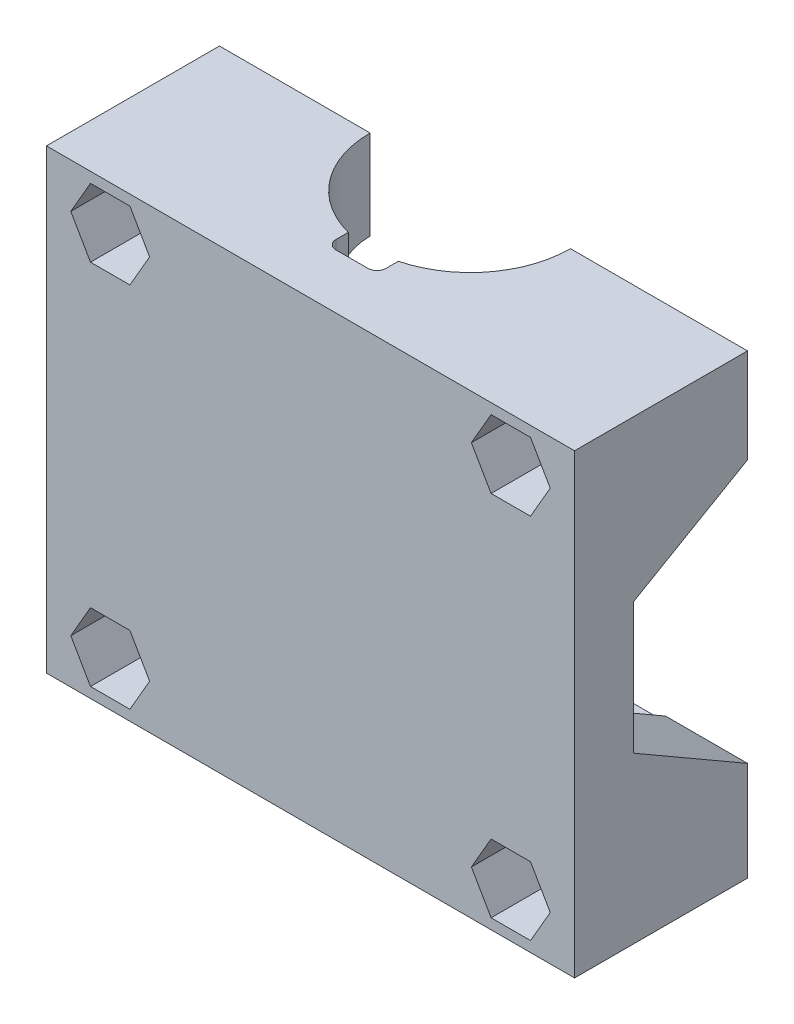
SolidWorks part; units mm, degrees
ref_plane "Front Plane" through (0, 0, 0) normal (0, 0, 1) x (1, 0, 0)
ref_plane "Top Plane" through (0, 0, 0) normal (0, 1, 0) x (1, 0, 0)
ref_plane "Right Plane" through (0, 0, 0) normal (1, 0, 0) x (0, 0, -1)
sketch "Sketch1" plane through (0, 0, 0) normal (1, 0, 0) x (0, 0, -1)
  line L1 (-25.7738, -30) -> (-44.7738, -30)
  line L2 (-25.7738, -30) -> (-25.7738, 20.15)
  line L3 (-25.7738, 20.15) -> (-44.7738, 20.15)
  line L4 (-44.7738, -30) -> (-44.7738, 20.15)
  line L5 (-25.7738, 9.7838) -> (-38.2738, 2.5669)
  line L6 (-38.2738, 2.5669) -> (-38.2738, -11.8669)
  line L7 (-38.2738, -11.8669) -> (-25.7738, -19.0838)
  line L8 (-25.7738, -19.0838) -> (-13.2738, -11.8669)
  line L9 (-13.2738, -11.8669) -> (-13.2738, 2.5669)
  line L10 (-13.2738, 2.5669) -> (-25.7738, 9.7838)
  circle A0 centre (-25.7738, -4.65) radius 12.5 construction
  dimension "D1" = 12.5
  dimension "D2" = 50.15
  dimension "D3" = 19
extrude "Boss-Extrude1" add sketch "Sketch1" along normal up to surface (29 mm away) and the other way up to surface (29 mm away) contours L7 L6 L5 L2 L3 L4 L1
sketch "Sketch2" plane through (0, 0, 0) normal (1, 0, 0) x (0, 0, -1)
  circle A0 centre (-25.7738, -4.65) radius 15
  dimension "D1" = 30
extrude "Cut-Extrude1" cut sketch "Sketch2" along normal blind 20 and the other way through all
sketch "Sketch3" plane through (0, 20.15, 0) normal (0, 1, 0) x (1, 0, 0)
  line L0 (29, -25.7738) -> (-29, -25.7738) construction
  line L1 (1.3, -25.7738) -> (-4.2, -25.7738)
  line L2 (1.3, -25.7738) -> (1.3, -37.7738)
  line L3 (0.3, -38.7738) -> (-3.2, -38.7738)
  line L4 (-4.2, -25.7738) -> (-4.2, -37.7738)
  line L6 (1.3, -15.1231) -> (1.3, -13.7738) construction
  line L7 (-4.2, -15.1231) -> (-4.2, -13.7738) construction
  circle A0 centre (-1.45, -25.7738) radius 11
  arc A1 (-3.2, -38.7738) -> (-4.2, -37.7738) centre (-3.2, -37.7738) cw
  arc A2 (1.3, -37.7738) -> (0.3, -38.7738) centre (0.3, -37.7738) cw
  line M10 (29, -25.7738) -> (-29, -25.7738)
  dimension "D2" = 22
  dimension "D3" = 1
  dimension "D1" = 13
extrude "Cut-Extrude2" cut sketch "Sketch3" against normal blind 18 contours L2 A0 M10 | L4 A0 L2 M10 | A0 L4 M10 | A2 L2 A0 L4 A1 L3
sketch "Sketch4" plane through (0, 0, 25.7738) normal (0, 0, -1) x (-1, 0, 0)
  circle A0 centre (-22, 15.2556) radius 3 construction
  circle A1 centre (-22, -25.1056) radius 3 construction
  circle A2 centre (22, -25.1056) radius 3 construction
  circle A3 centre (22, 15.2556) radius 3 construction
  circle A4 centre (-22, 15.2556) radius 3
  circle A5 centre (-22, -25.1056) radius 3
  circle A6 centre (22, -25.1056) radius 3
  circle A7 centre (22, 15.2556) radius 3
extrude "Cut-Extrude3" cut sketch "Sketch4" against normal through all
sketch "Sketch5" plane through (0, 0, 44.7738) normal (0, 0, 1) x (1, 0, 0)
  line L1 (-19.8349, -21.3556) -> (-24.1651, -21.3556)
  line L2 (-24.1651, -21.3556) -> (-26.3301, -25.1056)
  line L3 (-26.3301, -25.1056) -> (-24.1651, -28.8556)
  line L4 (-24.1651, -28.8556) -> (-19.8349, -28.8556)
  line L5 (-19.8349, -28.8556) -> (-17.6699, -25.1056)
  line L6 (-17.6699, -25.1056) -> (-19.8349, -21.3556)
  line L7 (-19.8349, 11.5056) -> (-17.6699, 15.2556)
  line L8 (-17.6699, 15.2556) -> (-19.8349, 19.0056)
  line L9 (-19.8349, 19.0056) -> (-24.1651, 19.0056)
  line L10 (-24.1651, 19.0056) -> (-26.3301, 15.2556)
  line L11 (-26.3301, 15.2556) -> (-24.1651, 11.5056)
  line L12 (-24.1651, 11.5056) -> (-19.8349, 11.5056)
  line L13 (17.6699, 15.2556) -> (19.8349, 11.5056)
  line L14 (19.8349, 11.5056) -> (24.1651, 11.5056)
  line L15 (24.1651, 11.5056) -> (26.3301, 15.2556)
  line L16 (26.3301, 15.2556) -> (24.1651, 19.0056)
  line L17 (24.1651, 19.0056) -> (19.8349, 19.0056)
  line L18 (19.8349, 19.0056) -> (17.6699, 15.2556)
  line L19 (24.1651, -21.3556) -> (19.8349, -21.3556)
  line L20 (19.8349, -21.3556) -> (17.6699, -25.1056)
  line L21 (17.6699, -25.1056) -> (19.8349, -28.8556)
  line L22 (19.8349, -28.8556) -> (24.1651, -28.8556)
  line L23 (24.1651, -28.8556) -> (26.3301, -25.1056)
  line L24 (26.3301, -25.1056) -> (24.1651, -21.3556)
  circle A0 centre (-22, 15.2556) radius 3.75 construction
  circle A1 centre (22, 15.2556) radius 3.75 construction
  circle A2 centre (22, -25.1056) radius 3.75 construction
  circle A9 centre (-22, -25.1056) radius 3.75 construction
  dimension "D1" = 7.5
extrude "Cut-Extrude4" cut sketch "Sketch5" against normal blind 10
